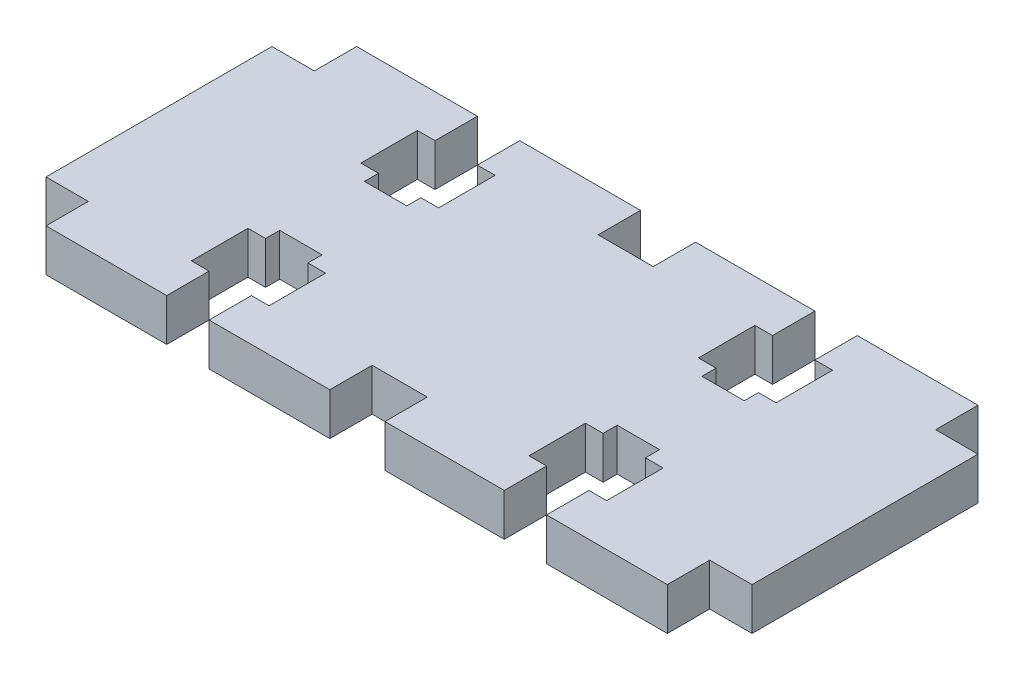
SolidWorks part; units mm, degrees
ref_plane "前视基准面" through (0, 0, 0) normal (0, 0, 1) x (1, 0, 0)
ref_plane "上视基准面" through (0, 0, 0) normal (0, 1, 0) x (1, 0, 0)
ref_plane "右视基准面" through (0, 0, 0) normal (1, 0, 0) x (0, 0, -1)
other "Configuration Table"
sketch "草图1" plane through (0, 0, 0) normal (0, 1, 0) x (1, 0, 0)
  line L0 (25, 0) -> (25, -16)
  line L1 (0, 0) -> (50, 0)
  line L2 (0, 0) -> (0, -16)
  line L3 (0, -16) -> (50, -16)
  line L4 (50, 0) -> (50, -16)
  line L5 (3, -16) -> (23.0981, -16)
  line L6 (3, -16) -> (3, -19)
  line L7 (3, -19) -> (23.0981, -19)
  line L8 (23.0981, -16) -> (23.0981, -19)
  line L13 (38.4509, -11) -> (35.4509, -11)
  line L14 (11.5491, -19) -> (14.5491, -19)
  line L19 (11.5491, -19) -> (11.5491, -11)
  line L20 (11.5491, -11) -> (14.5491, -11)
  line L29 (47, -19) -> (27, -19)
  line L30 (27, -16) -> (27, -19)
  line L31 (47, -16) -> (27, -16)
  line L32 (47, -16) -> (47, -19)
  line L33 (0, -8) -> (50, -8)
  line L50 (47, 0) -> (47, 3)
  line L51 (47, 0) -> (27, 0)
  line L52 (27, 0) -> (27, 3)
  line L53 (47, 3) -> (27, 3)
  line L54 (3, 3) -> (23.0981, 3)
  line L55 (23.0981, 0) -> (23.0981, 3)
  line L56 (3, 0) -> (23.0981, 0)
  line L57 (3, 0) -> (3, 3)
  line L58 (14.5491, -19) -> (14.5491, -11)
  line L59 (10.2991, -12) -> (15.7991, -12)
  line L60 (10.2991, -12) -> (10.2991, -16)
  line L61 (10.2991, -16) -> (15.7991, -16)
  line L62 (15.7991, -12) -> (15.7991, -16)
  line L63 (35.4509, -19) -> (35.4509, -11)
  line L64 (38.4509, -19) -> (35.4509, -19)
  line L65 (38.4509, -19) -> (38.4509, -11)
  line L66 (39.7009, -16) -> (34.2009, -16)
  line L67 (34.2009, -12) -> (34.2009, -16)
  line L68 (39.7009, -12) -> (34.2009, -12)
  line L69 (39.7009, -12) -> (39.7009, -16)
  line L70 (39.7009, -4) -> (39.7009, 0)
  line L71 (39.7009, -4) -> (34.2009, -4)
  line L72 (34.2009, -4) -> (34.2009, 0)
  line L73 (39.7009, 0) -> (34.2009, 0)
  line L74 (38.4509, 3) -> (38.4509, -5)
  line L75 (38.4509, 3) -> (35.4509, 3)
  line L76 (35.4509, 3) -> (35.4509, -5)
  line L77 (38.4509, -5) -> (35.4509, -5)
  line L78 (10.2991, 0) -> (15.7991, 0)
  line L79 (15.7991, -4) -> (15.7991, 0)
  line L80 (10.2991, -4) -> (15.7991, -4)
  line L81 (10.2991, -4) -> (10.2991, 0)
  line L82 (11.5491, -5) -> (14.5491, -5)
  line L83 (14.5491, 3) -> (14.5491, -5)
  line L84 (11.5491, 3) -> (14.5491, 3)
  line L85 (11.5491, 3) -> (11.5491, -5)
  point P15 (13.0491, -19)
  dimension "D3" = 3
  dimension "D4" = 8
  dimension "D1" = 50
  dimension "D2" = 16
  dimension "D6" = 4
  dimension "D7" = 3
  dimension "D8" = 3
  dimension "D9" = 2.75
  dimension "D10" = 0
  dimension "D11" = 1.5
  dimension "D5" = 5.5
extrude "凸台-拉伸1" add sketch "草图1" along normal blind 3 contours L85 L80 L81 L1 L2 L33 L0 L79 L83 L82 | L59 L62 L5 L3 L0 L33 L2 L60 L19 L20 L58 | L58 L7 L8 L5 L3 | L7 L19 L5 L3 L6 | L85 L54 L57 L1 L56 | L54 L83 L78 L1 L55 | L76 L53 L52 L1 L51 | L53 L74 L73 L51 L50 | L74 L77 L76 L71 L72 L1 L0 L33 L4 L51 L70 | L68 L69 L31 L3 L4 L33 L0 L67 L63 L13 L65 | L29 L63 L31 L3 L30 | L65 L29 L32 L31 L3
